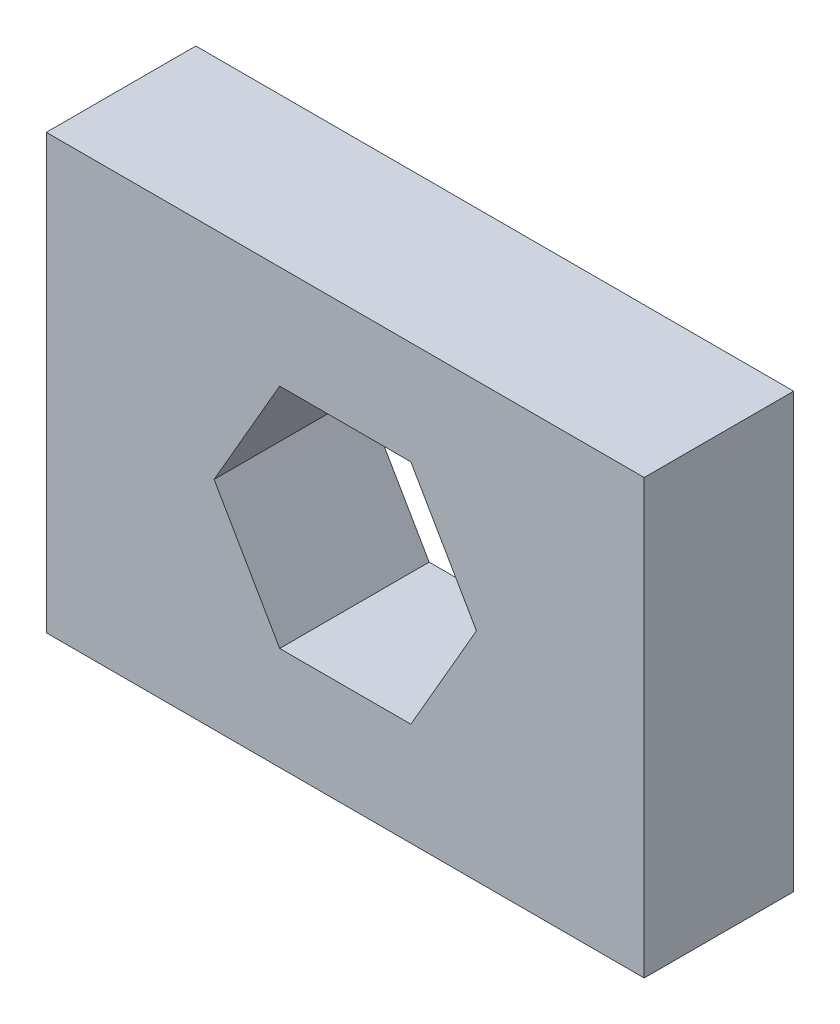
SolidWorks part; units mm, degrees
ref_plane "Plan de face" through (0, 0, 0) normal (0, 0, 1) x (1, 0, 0)
ref_plane "Plan de dessus" through (0, 0, 0) normal (0, 1, 0) x (1, 0, 0)
ref_plane "Plan de droite" through (0, 0, 0) normal (1, 0, 0) x (0, 0, -1)
sketch "Esquisse1" plane through (0, 0, 0) normal (0, 0, 1) x (1, 0, 0)
  line L0 (0, 7.25) -> (20, 7.25) construction
  line L1 (0, 0) -> (20, 0)
  line L2 (0, 0) -> (0, 14.5)
  line L3 (0, 14.5) -> (20, 14.5)
  line L4 (20, 0) -> (20, 14.5)
  line L6 (14.3879, 7.25) -> (12.1939, 11.05)
  line L7 (12.1939, 11.05) -> (7.8061, 11.05)
  line L8 (7.8061, 11.05) -> (5.6121, 7.25)
  line L9 (5.6121, 7.25) -> (7.8061, 3.45)
  line L10 (7.8061, 3.45) -> (12.1939, 3.45)
  line L11 (12.1939, 3.45) -> (14.3879, 7.25)
  circle A0 centre (10, 7.25) radius 3.8 construction
  dimension "D1" = 7.6
  dimension "D2" = 14.5
  dimension "D3" = 20
extrude "Boss.-Extru.1" add sketch "Esquisse1" along normal blind 5
